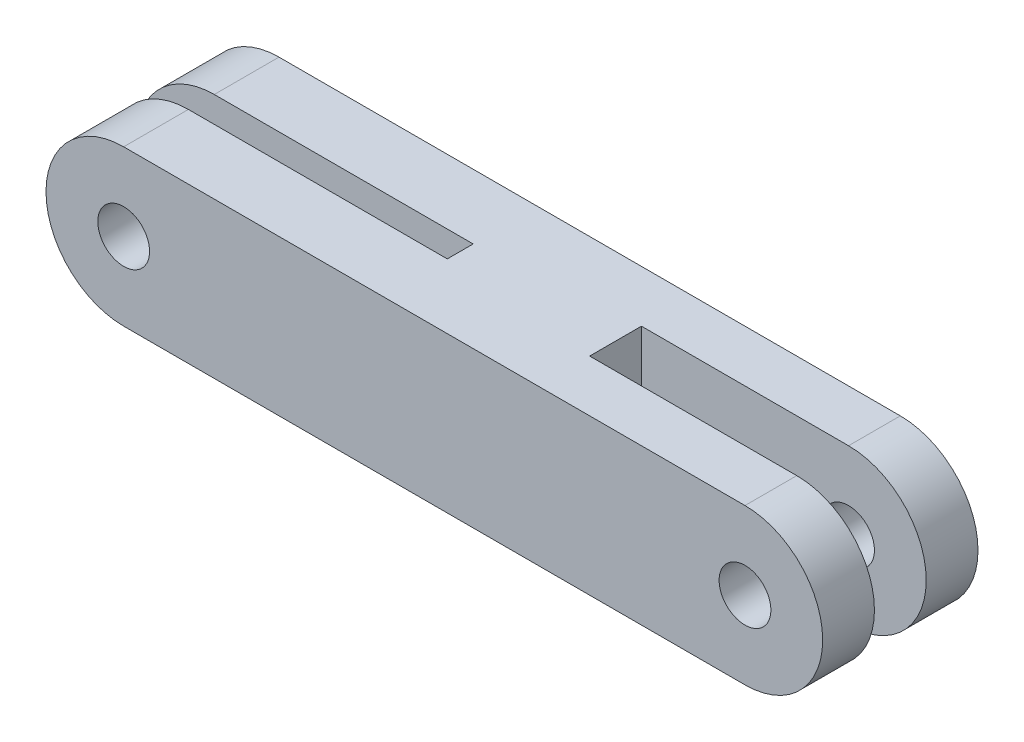
SolidWorks part; units mm, degrees
material "PVC Rigid"
ref_plane "Front Plane" through (0, 0, 0) normal (0, 0, 1) x (1, 0, 0)
ref_plane "Top Plane" through (0, 0, 0) normal (0, 1, 0) x (1, 0, 0)
ref_plane "Right Plane" through (0, 0, 0) normal (1, 0, 0) x (0, 0, -1)
sketch "Sketch1" plane through (0, 0, 0) normal (0, 0, 1) x (1, 0, 0)
  line L1 (-104.4163, 20.7238) -> (47.9837, 20.7238)
  line L3 (-104.4163, -17.3762) -> (47.9837, -17.3762)
  arc A0 (-104.4163, 20.7238) -> (-104.4163, -17.3762) centre (-104.4163, 1.6738) ccw
  arc A1 (47.9837, 20.7238) -> (47.9837, -17.3762) centre (47.9837, 1.6738) cw
  circle A3 centre (47.9837, 1.6738) radius 6.35
  circle A4 centre (-104.4163, 1.6738) radius 7.22
  point P6 (-123.4663, 1.6738)
  point P7 (67.0337, 1.6738)
  dimension "D3" = 19.05
  dimension "D5" = 19.05
  dimension "D1" = 190.5
  dimension "D2" = 38.1
extrude "Boss-Extrude1" add sketch "Sketch1" along normal blind 38.1
sketch "Sketch2" plane through (0, 0, 0) normal (0, 0, 1) x (1, 0, 0)
  line L1 (-117.1163, 14.3738) -> (-66.3163, 14.3738)
  line L2 (-117.1163, 14.3738) -> (-117.1163, -11.0262)
  line L3 (-117.1163, -11.0262) -> (-66.3163, -11.0262)
  line L4 (-66.3163, 14.3738) -> (-66.3163, -11.0262)
  circle A3 centre (-104.4163, 1.6738) radius 7.22 construction
  dimension "D3" = 12.7
  dimension "D4" = 12.7
  dimension "D1" = 50.8
  dimension "D2" = 25.4
extrude "Cut-Extrude1" cut sketch "Sketch2" along normal blind 6.35
sketch "Sketch4" plane through (0, 20.7238, 0) normal (0, 1, 0) x (1, 0, 0)
  line L0 (47.9837, 0) -> (-104.4163, 0) construction
  line L1 (-40.9163, -22.225) -> (-117.1163, -22.225)
  line L2 (-40.9163, -22.225) -> (-40.9163, -15.875)
  line L3 (-40.9163, -15.875) -> (-117.1163, -15.875)
  line L4 (-117.1163, -22.225) -> (-117.1163, -15.875)
  line L6 (-104.4163, -38.1) -> (-104.4163, 0) construction
  point P6 (-117.1163, -19.05)
  dimension "D1" = 15.875
  dimension "D2" = 76.2
  dimension "D3" = 6.35
  dimension "D4" = 63.5
sketch "Sketch5" plane through (0, 0, 0) normal (0, 1, 0) x (1, 0, 0)
  line L0 (47.9837, -38.1) -> (47.9837, 0) construction
  line L1 (-2.8163, -12.7) -> (73.3837, -12.7)
  line L2 (-2.8163, -12.7) -> (-2.8163, -25.4)
  line L3 (-2.8163, -25.4) -> (73.3837, -25.4)
  line L4 (73.3837, -12.7) -> (73.3837, -25.4)
  line L5 (47.9837, 0) -> (-104.4163, 0) construction
  dimension "D1" = 50.8
  dimension "D2" = 76.2
  dimension "D3" = 12.7
  dimension "D4" = 12.7
extrude "Cut-Extrude2" cut sketch "Sketch5" against normal through all both and the other way through all
extrude "Cut-Extrude3" cut sketch "Sketch4" against normal blind 31.75
sketch "Sketch6" plane through (0, 0, 38.1) normal (0, 0, -1) x (-1, 0, 0)
  circle A0 centre (104.4163, 1.6738) radius 6.35
extrude "Extrude-Thin1" add sketch "Sketch6" along direction (0, 0, 1) on the side of the normal offset from surface (12.7 mm away) 12.7 thin contours A0
sketch "Sketch7" plane through (0, 20.7238, 0) normal (0, 1, 0) x (1, 0, 0)
  line L0 (47.9837, -38.1) -> (-104.4163, -38.1) construction
  line L1 (-134.7315, -15.875) -> (-102.0318, -15.875)
  line L2 (-134.7315, -15.875) -> (-134.7315, -22.225)
  line L3 (-134.7315, -22.225) -> (-102.0318, -22.225)
  line L4 (-102.0318, -15.875) -> (-102.0318, -22.225)
  dimension "D1" = 6.35
  dimension "D2" = 15.875
extrude "Cut-Extrude4" cut sketch "Sketch7" against normal blind 19.05
